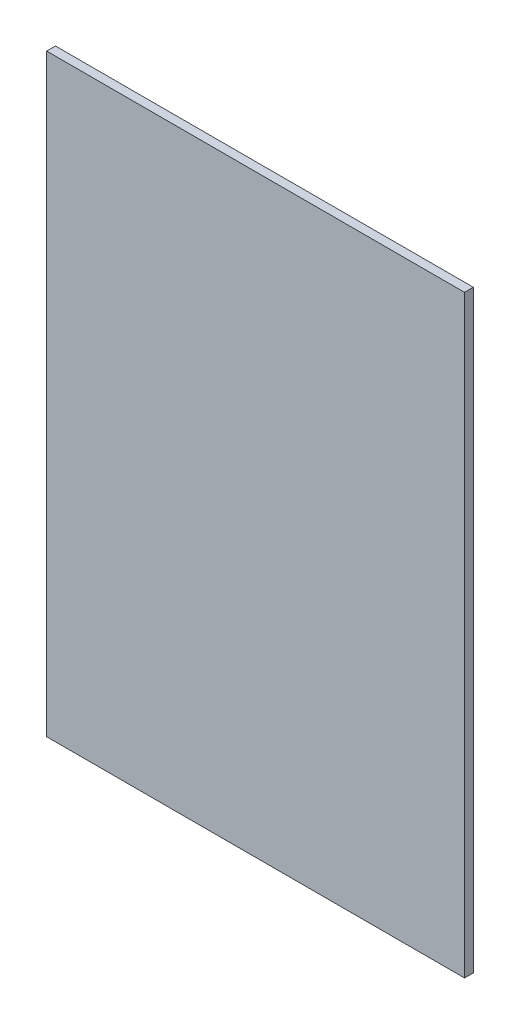
SolidWorks part; units mm, degrees
ref_plane "Front Plane" through (0, 0, 0) normal (0, 0, 1) x (1, 0, 0)
ref_plane "Top Plane" through (0, 0, 0) normal (0, 1, 0) x (1, 0, 0)
ref_plane "Right Plane" through (0, 0, 0) normal (1, 0, 0) x (0, 0, -1)
sketch "Sketch1" plane through (0, 0, 0) normal (0, 0, 1) x (1, 0, 0)
  line L1 (-47.5, 67.5) -> (47.5, 67.5)
  line L2 (-47.5, 67.5) -> (-47.5, -67.5)
  line L3 (-47.5, -67.5) -> (47.5, -67.5)
  line L4 (47.5, 67.5) -> (47.5, -67.5)
  line L5 (-47.5, 67.5) -> (47.5, -67.5) construction
  line L6 (-47.5, -67.5) -> (47.5, 67.5) construction
  point P0 (0, 0)
  dimension "D1" = 135
  dimension "D2" = 95
extrude "Boss-Extrude1" add sketch "Sketch1" along normal blind 2
